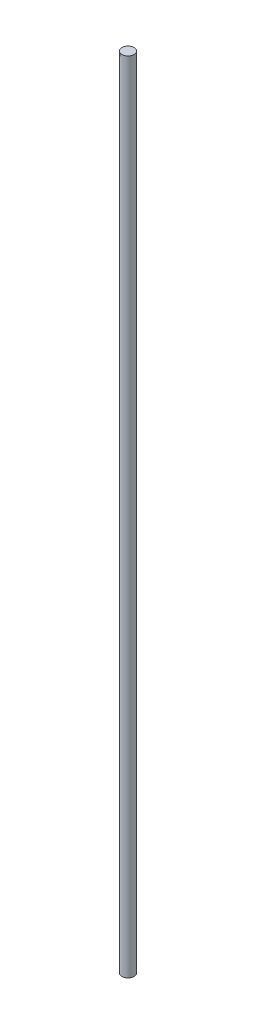
SolidWorks part; units mm, degrees
ref_plane "Front Plane" through (0, 0, 0) normal (0, 0, 1) x (1, 0, 0)
ref_plane "Top Plane" through (0, 0, 0) normal (0, 1, 0) x (1, 0, 0)
ref_plane "Right Plane" through (0, 0, 0) normal (1, 0, 0) x (0, 0, -1)
sketch "Sketch1" plane through (0, 0, 0) normal (0, 1, 0) x (1, 0, 0)
  circle A0 centre (0, 0) radius 3.05
extrude "Boss-Extrude1" add sketch "Sketch1" along normal blind 400
sketch "Sketch2" plane through (0, 400, 0) normal (0, 1, 0) x (1, 0, 0)
